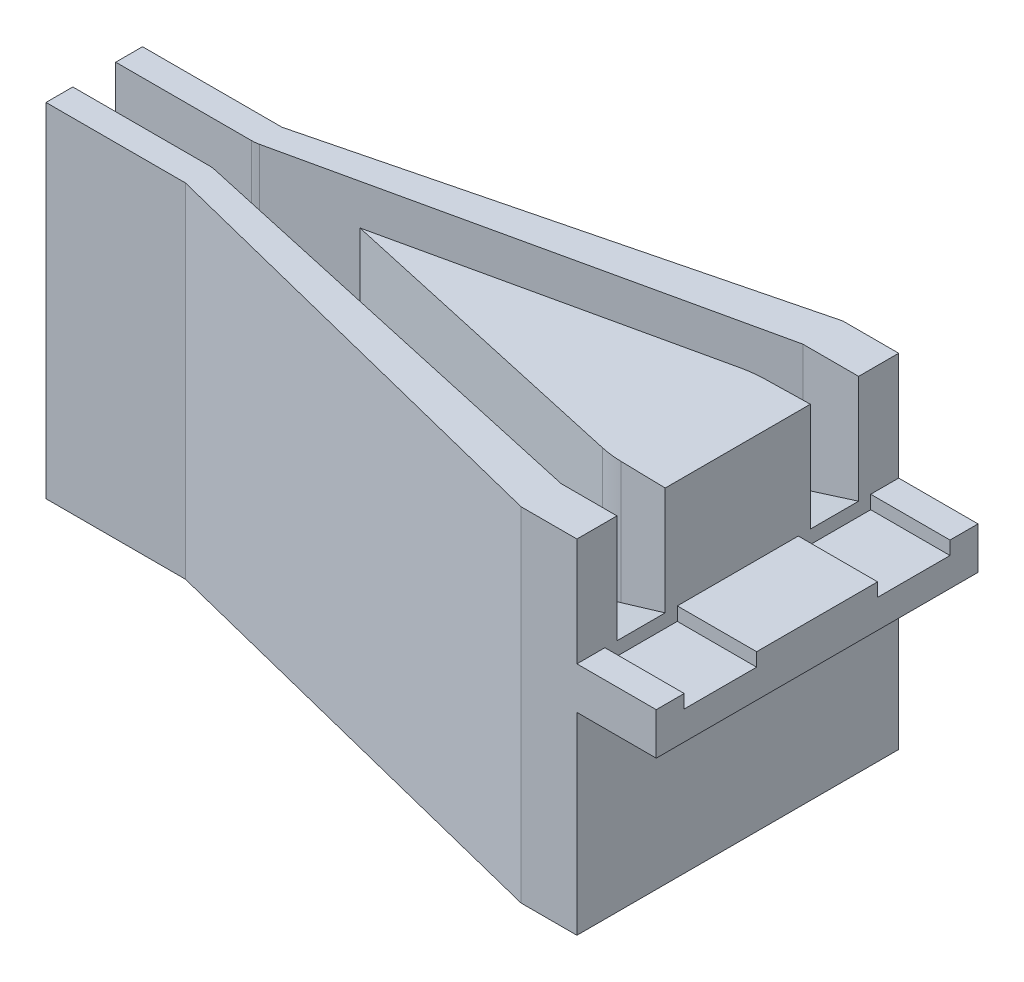
SolidWorks part; units mm, degrees
ref_plane "Front Plane" through (0, 0, 0) normal (0, 0, 1) x (1, 0, 0)
ref_plane "Top Plane" through (0, 0, 0) normal (0, 1, 0) x (1, 0, 0)
ref_plane "Right Plane" through (0, 0, 0) normal (1, 0, 0) x (0, 0, -1)
sketch "Sketch1" plane through (0, 0, 0) normal (0, 1, 0) x (1, 0, 0)
  line L1 (-76.2, 38.1) -> (76.2, 38.1)
  line L2 (-76.2, 38.1) -> (-76.2, -38.1)
  line L3 (-76.2, -38.1) -> (76.2, -38.1)
  line L4 (76.2, 38.1) -> (76.2, -38.1)
  line L5 (-76.2, 38.1) -> (76.2, -38.1) construction
  line L6 (-76.2, -38.1) -> (76.2, 38.1) construction
  point P0 (0, 0)
  dimension "D1" = 152.4
  dimension "D2" = 76.2
extrude "Boss-Extrude1" add sketch "Sketch1" along normal blind 81.28
sketch "Sketch2" plane through (0, 81.28, 0) normal (0, 1, 0) x (1, 0, 0)
  line L0 (-76.2, 0) -> (-76.2, 5.08)
  line L1 (-76.2, 38.1) -> (-76.2, -38.1) construction
  line L2 (-76.2, 0) -> (-76.2, -5.08)
  line L3 (-76.2, 5.08) -> (-43.18, 5.08)
  line L4 (-76.2, -5.08) -> (-43.18, -5.08)
  line L5 (-43.18, 5.08) -> (62.9783, 28.6147)
  line L6 (-43.18, -5.08) -> (62.9783, -28.6147)
  line L7 (-13.2852, 0) -> (62.9783, -16.9072)
  line L8 (-13.2852, 0) -> (62.9783, 16.9072)
  line L9 (62.9783, 28.6147) -> (76.2, 28.6147)
  line L10 (76.2, -38.1) -> (76.2, 38.1) construction
  line L11 (62.9783, 16.9072) -> (76.2, 17.1847)
  line L12 (76.2, 17.1847) -> (76.2, 28.6147)
  line L13 (62.9783, -16.9072) -> (76.2, -17.1847)
  line L14 (76.2, -17.1847) -> (76.2, -28.6147)
  line L15 (76.2, -28.6147) -> (62.9783, -28.6147)
  point P13 (76.2, 18.4103)
  point P16 (62.9783, -28.6147)
  dimension "D1" = 5.08
  dimension "D2" = 5.08
  dimension "D3" = 33.02
  dimension "D4" = 12.5
  dimension "D5" = 12.5
  dimension "D6" = 11.43
  dimension "D7" = 11.43
  dimension "D8" = 13.2217
  dimension "D9" = 11.43
extrude "Cut-Extrude1" cut sketch "Sketch2" against normal offset from surface (73.66 mm away) 7.62 up to face at (0, 0, 0)
sketch "Sketch4" plane through (0, 7.62, 0) normal (0, -1, 0) x (-1, 0, 0)
  line L0 (-76.2, 38.1) -> (76.2, 38.1) construction
  line L1 (76.2, -38.1) -> (-101.6, -38.1)
  line L2 (76.2, -38.1) -> (76.2, 38.1)
  line L3 (76.2, 38.1) -> (-101.6, 38.1)
  line L4 (-101.6, -38.1) -> (-101.6, 38.1)
  line L6 (-76.2, -38.1) -> (-76.2, 38.1) construction
  dimension "D1" = 25.4
revolve "Revolve1" add sketch "Sketch4" angle 17.5 about L2
sketch "Sketch3" plane through (0, 81.28, 0) normal (0, 1, 0) x (1, 0, 0)
  line L0 (62.9783, 38.1) -> (-76.2, 38.1)
  line L1 (-43.18, 11.43) -> (62.9783, 38.1)
  line L2 (-76.2, 38.1) -> (-76.2, 5.08) construction
  line L3 (-76.2, 38.1) -> (-76.2, 11.43)
  line L4 (-76.2, 11.43) -> (-43.18, 11.43)
  line L8 (-44.704, 0) -> (44.704, 0) construction
  line L12 (-76.2, -11.43) -> (-43.18, -11.43)
  line L13 (-76.2, -38.1) -> (-76.2, -11.43)
  line L14 (62.9783, -38.1) -> (-76.2, -38.1)
  line L15 (-43.18, -11.43) -> (62.9783, -38.1)
  line L16 (76.2, 38.1) -> (-76.2, 38.1) construction
  line L17 (-43.18, 5.08) -> (-76.2, 5.08) construction
  dimension "D1" = 6.35
extrude "Cut-Extrude2" cut sketch "Sketch3" against normal through all
sketch "Sketch5" plane through (0, 0, 0) normal (0, -1, 0) x (-1, 0, 0)
  line L1 (-76.2, 38.1) -> (-101.6, 38.1)
  line L2 (-76.2, 38.1) -> (-76.2, -38.1)
  line L3 (-76.2, -38.1) -> (-101.6, -38.1)
  line L4 (-101.6, 38.1) -> (-101.6, -38.1)
extrude "Cut-Extrude3" cut sketch "Sketch5" against normal blind 45.72
fillet "Fillet1" radius 7.62 2 edges at (-43.18, 49.6556, 5.08) (-43.18, 49.6556, -5.08)
fillet "Fillet2" radius 25.4 2 edges at (62.9783, 66.3914, -16.9072) (62.9783, 66.3914, 16.9072)
sketch "Sketch7" plane through (0, 0, 38.1) normal (0, 0, 1) x (1, 0, 0)
  line L1 (76.2, 55.6715) -> (97.5879, 55.6715)
  line L2 (76.2, 55.6715) -> (76.2, 61.0855)
  line L3 (76.2, 61.0855) -> (97.5879, 61.0855)
  line L4 (97.5879, 55.6715) -> (97.5879, 61.0855)
  dimension "D1" = 5.414
  dimension "D2" = 21.3879
extrude "Cut-Extrude5" cut sketch "Sketch7" against normal through all
sketch "Sketch8" plane through (0, 55.6715, 0) normal (0, 1, 0) x (1, 0, 0)
  line L1 (94.9838, 38.1) -> (97.4699, 38.1)
  line L2 (94.9838, 38.1) -> (94.9838, -38.1)
  line L3 (94.9838, -38.1) -> (97.4699, -38.1)
  line L4 (97.4699, 38.1) -> (97.4699, -38.1)
extrude "Cut-Extrude6" cut sketch "Sketch8" against normal through all
sketch "Sketch9" plane through (0, 55.6715, 0) normal (0, 1, 0) x (1, 0, 0)
  line L0 (76.2, 28.6147) -> (76.2, 17.1847) construction
  line L1 (76.2, -17.1847) -> (76.2, -28.6147) construction
  line L2 (76.2, 31.4722) -> (76.2, 14.3272)
  line L3 (76.2, 38.1) -> (76.2, 28.6147) construction
  line L4 (76.2, 17.1847) -> (76.2, -17.1847) construction
  line L5 (76.2, -14.3272) -> (76.2, -31.4722)
  line L6 (76.2, 31.4722) -> (94.9838, 31.4722)
  line L7 (94.9838, -38.1) -> (94.9838, 38.1) construction
  line L8 (94.9838, 31.4722) -> (94.9838, 14.3272)
  line L9 (94.9838, 14.3272) -> (76.2, 14.3272)
  line L10 (76.2, -14.3272) -> (94.9838, -14.3272)
  line L11 (94.9838, -14.3272) -> (94.9838, -31.4722)
  line L12 (94.9838, -31.4722) -> (76.2, -31.4722)
  point P0 (76.2, 22.8997)
  point P1 (76.2, -22.8997)
  point P20 (94.9838, -33.9465)
  point P21 (94.9838, -44.1872)
  point P22 (0, 0)
  dimension "D1" = 17.145
extrude "Cut-Extrude7" cut sketch "Sketch9" against normal blind 3.175
